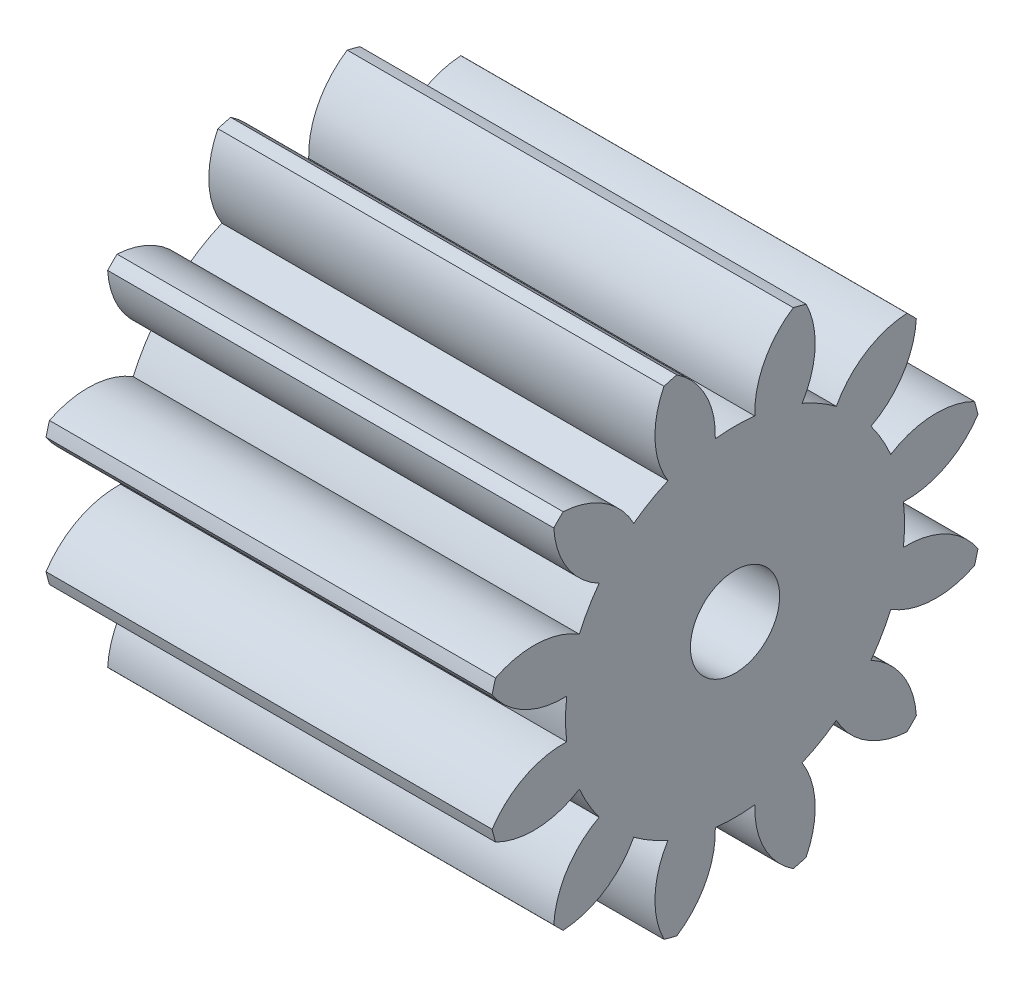
SolidWorks part; units mm, degrees
ref_plane "Plane1" through (0, 0, 0) normal (0, 0, 1) x (1, 0, 0)
ref_plane "Plane2" through (0, 0, 0) normal (0, 1, 0) x (1, 0, 0)
ref_plane "Plane3" through (0, 0, 0) normal (1, 0, 0) x (0, 0, -1)
sketch "HoldingSke" plane through (0, 0, 0) normal (0, 1, 0) x (1, 0, 0)
  line L0 (0, 0) -> (0.1223, -0.026)
  line L1 (-15, 0) -> (100, 0) construction
  line L2 (0, 0) -> (-2.1039, 2.3779)
  line L3 (0, 0) -> (-11.863, 4.5341)
  line L4 (0, 0) -> (8.4473, 1.7955)
  line L5 (0, 0) -> (-46.8476, -17.4728)
  line L6 (0, 0) -> (-82.8963, -55.9304)
  line L7 (-2.1039, 2.3779) -> (19.4211, 100.0338)
  line L8 (-76.2, 54.61) -> (-72.9, 54.61)
  line L9 (-71.009, 38.7566) -> (-53.1078, 45.2721)
  line L10 (-76.2, 71.12) -> (104.1128, 71.12)
  line L11 (0, 0) -> (-100, 0)
  line L12 (-76.2, 101.6) -> (-75.945, 101.6)
  line L13 (24.9733, 27.94) -> (52.9518, 28.4284)
  line L14 (24.9733, 27.94) -> (24.9743, 27.94)
  line L15 (24.9733, 27.94) -> (100.4006, 29.5858)
  line L16 (-63.627, -8) -> (-12.827, -8)
  circle A0 centre (0, 0) radius 10
  circle A1 centre (0, 0) radius 37.5
  circle A2 centre (0, 0) radius 37.5
  circle A3 centre (0, 0) radius 10
  dimension "MHD" = 75
  dimension "Hub_dia" = 75
  dimension "Bore" = 20
  dimension "MBD" = 20
  dimension "Num_teeth" = 12
  dimension "Pitch" = 0.125
  dimension "Overall_len" = 50
  dimension "Show_teeth" = 12
  dimension "Thickness" = 100
  dimension "OAL" = 100.0001
  dimension "T_dim" = 3.3
  dimension "Ap" = 20
  dimension "H" = 19.05
  dimension "Pitch_radius" = 180.3128
  dimension "Width" = 100
  dimension "Backlash" = 0.255
  dimension "Addendum_fac" = 1
  dimension "Dedendum_fac" = 1.25
  dimension "Clearance_fac" = 0.25
  dimension "Dedendum_add" = 0.001
  dimension "Module" = 8
sketch "BasProSke" plane through (0, 0, 0) normal (0, 1, 0) x (1, 0, 0)
  line L0 (-10, 0) -> (60, 0) construction
  line L1 (0, 0) -> (0, 56)
  line L2 (0, 0) -> (100, 0)
  line L3 (100, 0) -> (100, 56)
  line L4 (100, 56) -> (0, 56)
  dimension "Thickness" = 100
  dimension "Diameter" = 112
revolve "Base-Revolve" add sketch "BasProSke" angle 360 about L0
sketch "TooCutSke" plane through (0, 0, 0) normal (1, 0, 0) x (0, 0, -1)
  line L1 (0, 0) -> (0, 107) construction
  line L2 (0, 0) -> (-6.711, 47.5285) construction
  line L3 (0, 0) -> (-24.6634, 92.045) construction
  line L4 (-6.711, 47.5285) -> (-12.3317, 46.0225) construction
  arc A0 (4.4295, 37.7399) -> (-4.4295, 37.7399) centre (0, 0) ccw
  arc A1 (13.0788, 54.4774) -> (-13.0788, 54.4774) centre (0, 0) ccw
  circle A2 centre (0, 0) radius 48 construction
  circle A3 centre (0, 0) radius 45.1052 construction
  arc A4 (-4.4295, 37.7399) -> (-13.0788, 54.4774) centre (-23.6172, 38.428) ccw
  arc A5 (13.0788, 54.4774) -> (4.4295, 37.7399) centre (23.6172, 38.428) ccw
  dimension "Root_dia" = 75.998
  dimension "Overcut_dia" = 112.0508
  dimension "Pitch_dia" = 96
  dimension "Base_dia" = 90.2105
  dimension "Flank_rad" = 19.2
  dimension "Half_ang" = 15
  dimension "Half_CT" = 5.819
extrude "ToothCut" cut sketch "TooCutSke" along normal through all
fillet "Breaks" [suppressed] radius 0.16
fillet "RootFillets" [suppressed] radius 2.001
pattern_circular "TeethCuts" count 12 over 360 about axis through (0, 0, 0) along (1, 0, 0) of "ToothCut", "RootFillets", "Breaks"
sketch "HubNeaOneSke" plane through (0, 0, 0) normal (-1, 0, 0) x (0, 0, 1)
  circle A0 centre (0, 0) radius 37.5
  dimension "Diameter" = 75
extrude "HubNearOne" [suppressed] add sketch "HubNeaOneSke" along normal blind 12.7001
sketch "HubNeaBotSke" plane through (0, 0, 0) normal (-1, 0, 0) x (0, 0, 1)
  circle A0 centre (0, 0) radius 37.5
  dimension "Diameter" = 75
extrude "HubNearBoth" [suppressed] add sketch "HubNeaBotSke" along normal blind 6.35
ref_plane "FarPln" through (100, 0, 0) normal (1, 0, 0) x (0, 0, -1)
sketch "HubFarSke" plane through (100, 0, 0) normal (1, 0, 0) x (0, 0, -1)
  circle A0 centre (0, 0) radius 37.5
  dimension "Diameter" = 75
extrude "HubFar" [suppressed] add sketch "HubFarSke" along normal blind 6.35
sketch "BorSke" plane through (0, 0, 0) normal (1, 0, 0) x (0, 0, -1)
  circle A0 centre (0, 0) radius 10
  dimension "Diameter" = 20
extrude "Bore" cut sketch "BorSke" along normal mid plane 200.0001
sketch "KeySke" plane through (0, 0, 0) normal (1, 0, 0) x (0, 0, -1)
  line L0 (-6, 0) -> (-6, 13.3)
  line L1 (-6, 13.3) -> (6, 13.3)
  line L2 (6, 13.3) -> (6, 0)
  line L3 (0, 0) -> (0, 34) construction
  line L4 (-6, 0) -> (6, 0)
  dimension "Offset" = 13.3
  dimension "Width" = 12
extrude "Keyway" [suppressed] cut sketch "KeySke" along normal mid plane 200.0001
pattern_circular "Keyway2" [suppressed] count 2 every 90 about axis through (-10, 0, 0) along (1, 0, 0)
sketch "Sketch1" plane through (0, 0, 0) normal (-1, 0, 0) x (0, 0, 1)
  point P0 (0, 0)
equation "' \"Module@HoldingSke\" = 6.35"
equation "' \"Num_teeth@HoldingSke\" = 12"
equation "' \"Ap@HoldingSke\" =  20"
equation "' \"Ap@HoldingSke\" = 20"
equation "' \"Width@HoldingSke\" = 0.5 * 25.4"
equation "' \"Hub_dia@HoldingSke\"= 1 * 25.4"
equation "' \"Hub_dia@HoldingSke\" = 1 * 25.4"
equation "' \"Overall_len@HoldingSke\" = 1.0 * 25.4"
equation "' \"Bore@HoldingSke\" = 0.75 * 25.4"
equation "' \"T_dim@HoldingSke\" = 0.1 * 25.4"
equation "' \"Width@KeySke\" = 0.25 * 25.4"
equation "' \"Show_teeth@HoldingSke\" = 13"
equation "' \"Backlash@HoldingSke\" = 0.009 * 25.4"
equation "' \"Addendum_fac@HoldingSke\" = 1.0"
equation "' \"Dedendum_fac@HoldingSke\" = 1.25"
equation "' \"Dedendum_add@HoldingSke\" = 0.00005 * 25.4"
equation "' \"Clearance_fac@HoldingSke\" = 0.25"
equation "\"Pitch@HoldingSke\" = 1 / \"Module@HoldingSke\""
equation "\"Overcut_dia@TooCutSke\" = (\"Num_teeth@HoldingSke\" + 2 * \"Addendum_fac@HoldingSke\") / \"Pitch@HoldingSke\" + 0.002 * 25.4"
equation "\"Pitch_dia@TooCutSke\" = \"Num_teeth@HoldingSke\" / \"Pitch@HoldingSke\""
equation "\"Base_dia@TooCutSke\" = \"Num_teeth@HoldingSke\" / \"Pitch@HoldingSke\" * cos((\"Ap@HoldingSke\"  * 3.14159265 / 180))"
equation "\"Root_dia@TooCutSke\" = (\"Num_teeth@HoldingSke\" + 2) / \"Pitch@HoldingSke\" - 2 * (\"Addendum_fac@HoldingSke\" + \"Dedendum_fac@HoldingSke\") / \"Pitch@HoldingSke\" - \"Dedendum_add@HoldingSke\" * 2"
equation "\"Half_ang@TooCutSke\" = 180 / \"Num_teeth@HoldingSke\""
equation "\"Half_CT@TooCutSke\" = \"Num_teeth@HoldingSke\" / \"Pitch@HoldingSke\" * sin((3.14159265 / 2 / \"Num_teeth@HoldingSke\")) / 2 - 7 * \"Backlash@HoldingSke\" / 4"
equation "\"Flank_rad@TooCutSke\" = \"Num_teeth@HoldingSke\" / \"Pitch@HoldingSke\" / 5"
equation "\"Radius@RootFillets\" = \"Clearance_fac@HoldingSke\" / \"Pitch@HoldingSke\" + \"Dedendum_add@HoldingSke\""
equation "\"Break_rad@Breaks\" = 0.02 / \"Pitch@HoldingSke\""
equation "\"Thickness@HoldingSke\" = \"Width@HoldingSke\""
equation "\"OAL@HoldingSke\" = \"Thickness@HoldingSke\""
equation "\"MHD@HoldingSke\" = (\"Num_teeth@HoldingSke\" + 2) / \"Pitch@HoldingSke\" - 2 * (\"Addendum_fac@HoldingSke\" + \"Dedendum_fac@HoldingSke\")  / \"Pitch@HoldingSke\" - \"Dedendum_add@HoldingSke\" * 2"
equation "\"MBD@HoldingSke\" = (\"Num_teeth@HoldingSke\" + 2) / \"Pitch@HoldingSke\" - 2 * (\"Addendum_fac@HoldingSke\" + \"Dedendum_fac@HoldingSke\")  / \"Pitch@HoldingSke\" - \"Dedendum_add@HoldingSke\" * 2 - 0.002 * 25.4"
equation "\"MHD@HoldingSke\" = ((sgn( \"MHD@HoldingSke\" - \"Hub_dia@HoldingSke\" )-1)*( \"MHD@HoldingSke\" - \"Hub_dia@HoldingSke\" ))/-2+ \"Hub_dia@HoldingSke\""
equation "\"MBD@HoldingSke\" = ((sgn( \"MBD@HoldingSke\" - \"Bore@HoldingSke\" )-1)*( \"MBD@HoldingSke\" - \"Bore@HoldingSke\" ))/-2+ \"Bore@HoldingSke\""
equation "\"OAL@HoldingSke\" = ((sgn( \"OAL@HoldingSke\" - \"Overall_len@HoldingSke\" )+1)*( \"OAL@HoldingSke\" - \"Overall_len@HoldingSke\" ))/2 + \"Overall_len@HoldingSke\" + 0.000002 * 25.4"
equation "\"Num_teeth@TeethCuts\" = int( \"Show_teeth@HoldingSke\" ) + 1"
equation "\"Num_teeth@TeethCuts\" = ((sgn( \"Num_teeth@TeethCuts\" - \"Num_teeth@HoldingSke\" )-1)*( \"Num_teeth@TeethCuts\" - \"Num_teeth@HoldingSke\" ))/-2+ \"Num_teeth@HoldingSke\""
equation "\"Num_teeth@TeethCuts\" = ((sgn( \"Num_teeth@TeethCuts\" - 2.0)+1)*( \"Num_teeth@TeethCuts\" - 2.0))/2 +2.0"
equation "\"Angle@TeethCuts\" = 360.0 / \"Num_teeth@HoldingSke\""
equation "\"Diameter@BasProSke\" = (\"Num_teeth@HoldingSke\" + 2 * \"Addendum_fac@HoldingSke\") / \"Pitch@HoldingSke\""
equation "\"Thickness@BasProSke\"  = \"Thickness@HoldingSke\""
equation "' \"Fillet_rad@BasProSke\" =  \"Thickness@HoldingSke\" * 0.05"
equation "' \"Fillet_rad@BasProSke\" = \"Thickness@HoldingSke\" * 0.05"
equation "\"MHD@HoldingSke\" = ((sgn( \"MHD@HoldingSke\" - \"Root_dia@TooCutSke\" )-1)*( \"MHD@HoldingSke\" - \"Root_dia@TooCutSke\" ))/-2+ \"Root_dia@TooCutSke\""
equation "\"Diameter@HubNeaOneSke\" = \"MHD@HoldingSke\""
equation "\"Length@HubNearOne\" = \"OAL@HoldingSke\" - \"Thickness@BasProSke\""
equation "\"Diameter@HubNeaBotSke\" = \"MHD@HoldingSke\""
equation "\"Length@HubNearBoth\" = ( \"OAL@HoldingSke\" - \"Thickness@BasProSke\" ) / 2.0"
equation "\"Thickness@FarPln\" = \"Thickness@BasProSke\""
equation "\"Diameter@HubFarSke\" = \"MHD@HoldingSke\""
equation "\"Length@HubFar\" = ( \"OAL@HoldingSke\" - \"Thickness@BasProSke\" ) / 2.0"
equation "\"Diameter@BorSke\" = \"MBD@HoldingSke\""
equation "\"D1@Bore\" = \"OAL@HoldingSke\" * 2.0"
equation "\"D1@Keyway\" = \"OAL@HoldingSke\" * 2.0"
equation "\"Offset@KeySke\" = \"T_dim@HoldingSke\" + \"MBD@HoldingSke\" / 2.0"
